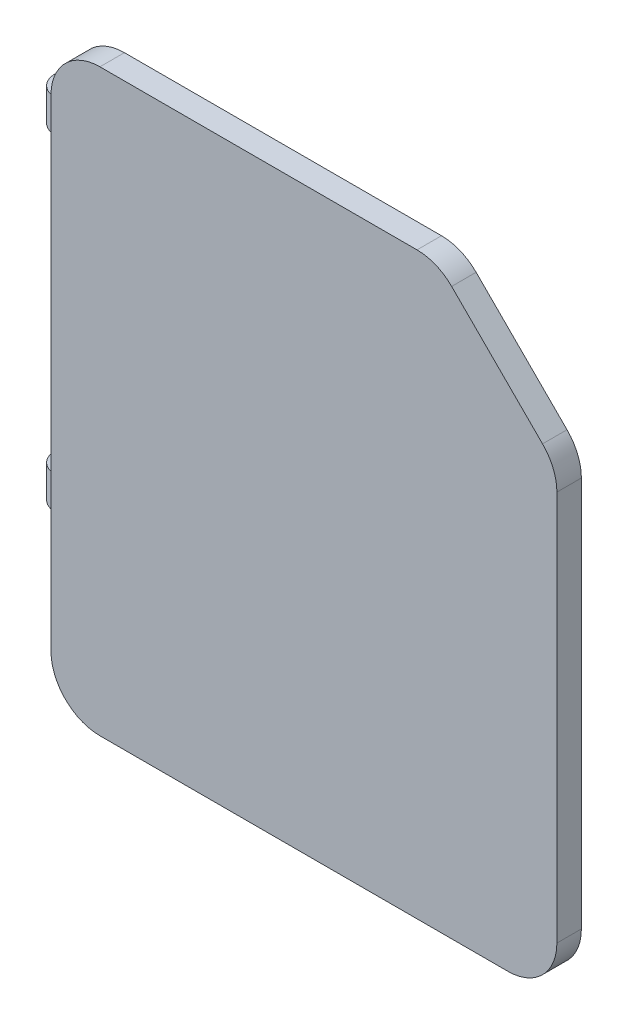
SolidWorks part; units mm, degrees
ref_plane "Front Plane" through (0, 0, 0) normal (0, 0, 1) x (1, 0, 0)
ref_plane "Top Plane" through (0, 0, 0) normal (0, 1, 0) x (1, 0, 0)
ref_plane "Right Plane" through (0, 0, 0) normal (1, 0, 0) x (0, 0, -1)
sketch "Sketch1" plane through (0, 0, 0) normal (0, 0, 1) x (1, 0, 0)
  line L0 (-238.7401, 0) -> (238.7401, 0) construction
  line L1 (0, 0) -> (0, 164.0151) construction
  line L2 (-155, -200) -> (-155, 155)
  line L3 (155, -200) -> (155, 155)
  line L4 (-155, 155) -> (155, 155)
  line L5 (-155, -200) -> (155, -200)
  line L6 (155, 81.7225) -> (81.7225, 155)
  line L7 (155, 81.7225) -> (48.3806, 81.7225) construction
  point P4 (0, 0)
  point P10 (-175, 0)
  dimension "D1" = 355
  dimension "D2" = 310
  dimension "D3" = 45
  dimension "D4" = 103.63
  dimension "D5" = 155
extrude "Boss-Extrude1" add sketch "Sketch1" along normal blind 15 contours L3 L6 L4 L2 L5
ref_plane "Plane1" through (0, 100, 0) normal (0, 1, 0) x (1, 0, 0)
ref_plane "Plane2" through (0, -100, 0) normal (0, 1, 0) x (1, 0, 0)
sketch "Sketch3" plane through (0, 100, 0) normal (0, 1, 0) x (1, 0, 0)
  line L0 (-155, 0) -> (-180, 0) construction
  line L1 (-180, 0) -> (-180, 12.5) construction
  line L2 (-180, 12.5) -> (-155, 12.5) construction
  line L3 (-155, 12.5) -> (-155, 0) construction
  line L4 (-167.5, 0) -> (-167.5, 12.5) construction
  line L5 (-167.5, 0) -> (-107.5, 0)
  line L6 (-162.5083, 23.9601) -> (-107.5, 0)
  circle A0 centre (-167.5, 12.5) radius 10
  circle A1 centre (-167.5, 12.5) radius 12.5
  dimension "D3" = 20
  dimension "D4" = 25
  dimension "D1" = 25
  dimension "D2" = 12.5
  dimension "D5" = 60
extrude "Boss-Extrude2" add sketch "Sketch3" along normal blind 10 and the other way blind 10 contours A1 L5 L6 | A1 A0
sketch "Sketch4" plane through (0, -100, 0) normal (0, 1, 0) x (1, 0, 0)
  line L0 (-155, 0) -> (-180, 0) construction
  line L1 (-180, 0) -> (-180, 12.5) construction
  line L2 (-180, 12.5) -> (-155, 12.5) construction
  line L3 (-155, 12.5) -> (-155, 0) construction
  line L4 (-167.5, 0) -> (-167.5, 12.5) construction
  line L5 (-162.5083, 23.9601) -> (-107.5, 0)
  line L7 (-107.5, 0) -> (-167.5, 0)
  line L8 (-155, -15) -> (-155, 0) construction
  line L9 (-155, 0) -> (81.7225, 0) construction
  circle A0 centre (-167.5, 12.5) radius 10
  circle A1 centre (-167.5, 12.5) radius 12.5
  dimension "D3" = 20
  dimension "D4" = 25
  dimension "D1" = 25
  dimension "D2" = 12.5
  dimension "D5" = 60
extrude "Boss-Extrude3" add sketch "Sketch4" along normal blind 10 and the other way blind 10 contours A1 A0 | A1 L7 L5
sketch "Sketch5" plane through (0, 0, 0) normal (0, 0, -1) x (-1, 0, 0)
  line L0 (-146.2132, 90.5093) -> (-90.5093, 146.2132)
  line L1 (-69.2961, 155) -> (125, 155)
  line L2 (155, 125) -> (155, -170)
  line L3 (125, -200) -> (-125, -200)
  line L4 (-155, -170) -> (-155, 69.2961)
  line L5 (-155, 69.2961) -> (-155, 81.7225)
  line L6 (-155, 81.7225) -> (-146.2132, 90.5093)
  line L7 (-90.5093, 146.2132) -> (-81.7225, 155)
  line L8 (-81.7225, 155) -> (-69.2961, 155)
  line L9 (125, 155) -> (155, 155)
  line L10 (155, 155) -> (155, 125)
  line L11 (125, -200) -> (155, -200)
  line L12 (155, -200) -> (155, -170)
  line L13 (-155, -170) -> (-155, -200)
  line L14 (-155, -200) -> (-125, -200)
  arc A0 (-125, -200) -> (-155, -170) centre (-125, -170) cw
  arc A1 (155, -170) -> (125, -200) centre (125, -170) cw
  arc A2 (125, 155) -> (155, 125) centre (125, 125) cw
  arc A3 (-90.5093, 146.2132) -> (-69.2961, 155) centre (-69.2961, 125) cw
  arc A4 (-146.2132, 90.5093) -> (-155, 69.2961) centre (-125, 69.2961) ccw
  point P12 (-155, -200)
  point P15 (155, -200)
  point P18 (155, 155)
  point P21 (-81.7225, 155)
  point P24 (-155, 81.7225)
  line M15 (155, 110) -> (155, 155)
  line M16 (155, 155) -> (-81.7225, 155)
  line M17 (-81.7225, 155) -> (-155, 81.7225)
  line M18 (-155, 81.7225) -> (-155, -200)
  line M19 (-155, -200) -> (155, -200)
  line M20 (155, -200) -> (155, -110)
  dimension "D1" = 30
extrude "Cut-Extrude1" cut sketch "Sketch5" against normal blind 46 contours A0 M19 M18 | A1 M20 M19 | A2 M16 M15 | A3 M17 M16 | A4 M17 M18
sketch "Sketch6" plane through (0, 0, 0) normal (0, 0, -1) x (-1, 0, 0)
  line L0 (0, 0) -> (-155, 0) construction
  line L1 (-155, -170) -> (-155, 69.2961) construction
  line L2 (-125, 0) -> (-125, -200) construction
  line L3 (125, -200) -> (-125, -200) construction
  circle A0 centre (-125, 40) radius 7.5
  circle A1 centre (-125, -40) radius 7.5
  dimension "D2" = 15
  dimension "D3" = 15
  dimension "D1" = 30
  dimension "D4" = 80
  dimension "D5" = 240
extrude "Boss-Extrude4" add sketch "Sketch6" along normal blind 10
sketch "Sketch7" plane through (0, 0, -10) normal (0, 0, -1) x (-1, 0, 0)
  line L0 (0, 0) -> (-155, 0) construction
  line L1 (-155, -170) -> (-155, 69.2961) construction
  line L2 (-125, 40) -> (-125, -40) construction
  line L3 (-125, 40) -> (-125, 56.5668) construction
  line L4 (-130, 50) -> (-120, 50)
  line L5 (-130, -50) -> (-120, -50)
  line L6 (-135, 45) -> (-135, -45)
  line L7 (-115, -45) -> (-115, 45)
  arc A0 (-120, -50) -> (-115, -45) centre (-120, -45) ccw
  arc A1 (-130, -50) -> (-135, -45) centre (-130, -45) cw
  arc A2 (-120, 50) -> (-115, 45) centre (-120, 45) cw
  arc A3 (-130, 50) -> (-135, 45) centre (-130, 45) ccw
  point P13 (-125, 50)
  point P17 (-115, -50)
  point P20 (-135, -50)
  point P23 (-115, 50)
  point P26 (-135, 50)
  dimension "D3" = 5
  dimension "D1" = 20
  dimension "D2" = 100
extrude "Boss-Extrude5" add sketch "Sketch7" along normal blind 5
